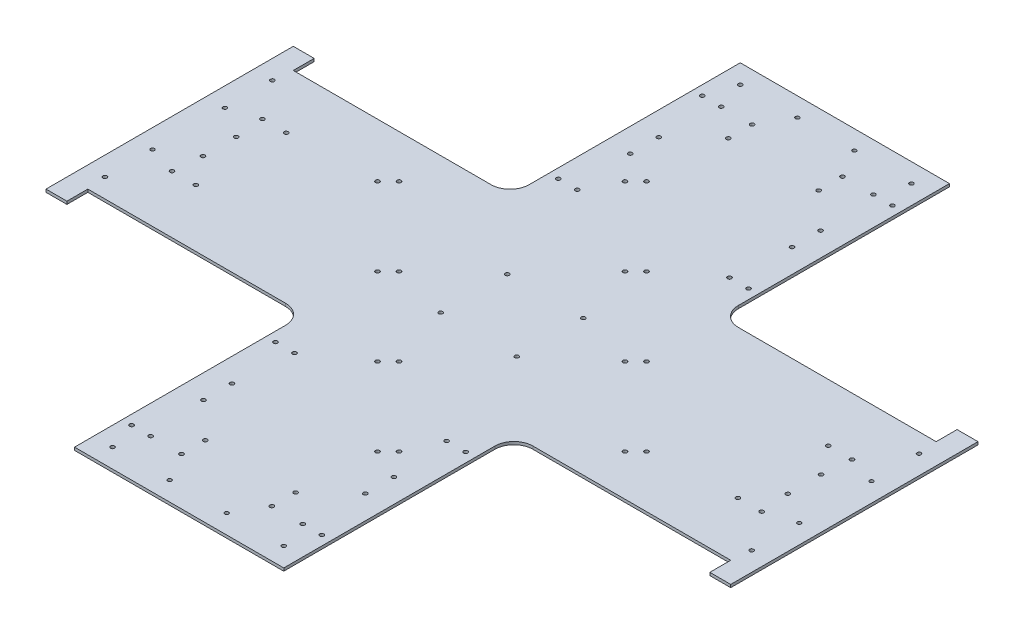
SolidWorks part; units mm, degrees
ref_plane "Front Plane" through (0, 0, 0) normal (0, 0, 1) x (1, 0, 0)
ref_plane "Top Plane" through (0, 0, 0) normal (0, 1, 0) x (1, 0, 0)
ref_plane "Right Plane" through (0, 0, 0) normal (1, 0, 0) x (0, 0, -1)
sketch "Sketch1" plane through (0, 0, 0) normal (0, 1, 0) x (1, 0, 0)
  line L0 (-110, 350) -> (-110, 108)
  line L1 (-110, 108) -> (-338, 108)
  line L2 (-338, 108) -> (-338, 130)
  line L3 (-338, 130) -> (-360, 130)
  line L4 (-360, 130) -> (-360, -130)
  line L5 (-360, 0) -> (1003.1457, 0) construction
  line L6 (0, 350) -> (0, -620.7989) construction
  line L7 (-338, -130) -> (-360, -130)
  line L8 (-338, -108) -> (-338, -130)
  line L9 (-110, -108) -> (-338, -108)
  line L10 (-110, 350) -> (110, 350)
  line L11 (-110, -350) -> (-110, -108)
  line L12 (-110, -350) -> (110, -350)
  line L13 (110, -350) -> (110, -108)
  line L14 (110, -108) -> (338, -108)
  line L15 (338, -108) -> (338, -130)
  line L16 (338, -130) -> (360, -130)
  line L17 (360, 130) -> (360, -130)
  line L18 (338, 130) -> (360, 130)
  line L19 (338, 108) -> (338, 130)
  line L20 (110, 108) -> (338, 108)
  line L21 (110, 350) -> (110, 108)
  point P17 (0, -350)
  dimension "D1" = 110
  dimension "D2" = 22
  dimension "D3" = 22
  dimension "D4" = 242
  dimension "D5" = 130
  dimension "D6" = 250
  dimension "D7" = 110
  dimension "D8" = 108
extrude "Boss-Extrude1" add sketch "Sketch1" along normal blind 3
sketch "Sketch2" plane through (0, 3, 0) normal (0, 1, 0) x (1, 0, 0)
  line L0 (360, -130) -> (360, 130) construction
  line L2 (338, 108) -> (110, 108) construction
  line L4 (0, 107.9437) -> (0, -458.275) construction
  line L5 (110, 108) -> (110, 350) construction
  line L6 (110, 350) -> (-110, 350) construction
  line L7 (-540.1841, 0) -> (-80.3508, 0) construction
  circle A0 centre (310, 47.5) radius 2.125
  circle A1 centre (285, 47.5) radius 2.125
  circle A2 centre (307.5, 17.5) radius 2.125
  circle A3 centre (307.5, -17.5) radius 2.125
  circle A4 centre (310, -47.5) radius 2.125
  circle A5 centre (285, -47.5) radius 2.125
  circle A6 centre (-285, -47.5) radius 2.125
  circle A7 centre (-310, -47.5) radius 2.125
  circle A8 centre (-307.5, -17.5) radius 2.125
  circle A9 centre (-307.5, 17.5) radius 2.125
  circle A10 centre (-285, 47.5) radius 2.125
  circle A11 centre (-310, 47.5) radius 2.125
  circle A13 centre (47.5, 300) radius 2.125
  circle A15 centre (47.5, 275) radius 2.125
  circle A16 centre (-47.5, 275) radius 2.125
  circle A17 centre (-47.5, 300) radius 2.125
  circle A18 centre (-47.5, -300) radius 2.125
  circle A19 centre (-47.5, -275) radius 2.125
  circle A20 centre (47.5, -275) radius 2.125
  circle A21 centre (47.5, -300) radius 2.125
  dimension "D1" = 4.25
  dimension "D2" = 4.25
  dimension "D3" = 4.25
  dimension "D4" = 4.25
  dimension "D5" = 4.25
  dimension "D6" = 4.25
  dimension "D15" = 4.25
  dimension "D16" = 4.25
  dimension "D7" = 50
  dimension "D8" = 25
  dimension "D9" = 95
  dimension "D10" = 35
  dimension "D11" = 60.5
  dimension "D12" = 90.5
  dimension "D13" = 52.5
  dimension "D14" = 110
  dimension "D17" = 50
  dimension "D18" = 25
  dimension "D19" = 62.5
  dimension "D20" = 108
extrude "Cut-Extrude1" cut sketch "Sketch2" against normal through all
sketch "Sketch3" plane through (0, 3, 0) normal (0, 1, 0) x (1, 0, 0)
  line L0 (360, -130) -> (360, 130) construction
  line L1 (338, 108) -> (110, 108) construction
  line L2 (-553.4456, 0) -> (-91.4299, 0) construction
  line L3 (0, 286.895) -> (0, -255.8046) construction
  line L4 (110, 108) -> (110, 350) construction
  line L5 (110, 350) -> (-110, 350) construction
  line L6 (-110, 350) -> (-110, 108) construction
  circle A0 centre (340, 38) radius 2
  circle A2 centre (340, -38) radius 2
  circle A3 centre (-340, -38) radius 2
  circle A4 centre (-340, 38) radius 2
  circle A5 centre (-30, 330) radius 2
  circle A7 centre (30, 330) radius 2
  circle A8 centre (30, -330) radius 2
  circle A9 centre (-30, -330) radius 2
  dimension "D1" = 4
  dimension "D6" = 4
  dimension "D7" = 80
  dimension "D2" = 20
  dimension "D3" = 70
  dimension "D4" = 108
  dimension "D5" = 110
  dimension "D8" = 20
extrude "Cut-Extrude2" cut sketch "Sketch3" against normal through all
sketch "Sketch5" plane through (0, 3, 0) normal (0, 1, 0) x (1, 0, 0)
  line L0 (110, 350) -> (-110, 350) construction
  line L1 (110, 108) -> (110, 350) construction
  line L2 (0, 224.365) -> (185.6725, 224.365) construction
  line L3 (90, 361.0488) -> (90, 126.2188) construction
  line L4 (0, 375.894) -> (0, 88.4107) construction
  line L5 (349.7475, 0) -> (-242.2654, 0) construction
  circle A0 centre (80, 300) radius 2.125
  circle A1 centre (80, 148.73) radius 2.125
  circle A2 centre (85.11, 239.365) radius 2.125
  circle A3 centre (85.11, 209.365) radius 2.125
  circle A4 centre (100, 148.73) radius 2.125
  circle A5 centre (100, 300) radius 2.125
  circle A6 centre (-100, 300) radius 2.125
  circle A7 centre (-100, 148.73) radius 2.125
  circle A8 centre (-85.11, 209.365) radius 2.125
  circle A9 centre (-85.11, 239.365) radius 2.125
  circle A10 centre (-80, 148.73) radius 2.125
  circle A11 centre (-80, 300) radius 2.125
  circle A12 centre (-80, -300) radius 2.125
  circle A13 centre (-80, -148.73) radius 2.125
  circle A14 centre (-85.11, -239.365) radius 2.125
  circle A15 centre (-85.11, -209.365) radius 2.125
  circle A16 centre (-100, -148.73) radius 2.125
  circle A17 centre (-100, -300) radius 2.125
  circle A18 centre (100, -300) radius 2.125
  circle A19 centre (100, -148.73) radius 2.125
  circle A20 centre (85.11, -209.365) radius 2.125
  circle A21 centre (85.11, -239.365) radius 2.125
  circle A22 centre (80, -148.73) radius 2.125
  circle A23 centre (80, -300) radius 2.125
  dimension "D1" = 4.25
  dimension "D2" = 4.25
  dimension "D6" = 4.25
  dimension "D7" = 4.25
  dimension "D3" = 151.27
  dimension "D4" = 50
  dimension "30" = 30
  dimension "D5" = 5.11
  dimension "D8" = 30
  dimension "D9" = 75.635
  dimension "D10" = 15
  dimension "D11" = 10
extrude "Cut-Extrude4" cut sketch "Sketch5" against normal blind 10
fillet "Fillet1" radius 20 4 edges at (110, 1.5, -108) (-110, 1.5, -108) (-110, 1.5, 108) (110, 1.5, 108)
sketch "Sketch6" plane through (0, 3, 0) normal (0, 1, 0) x (1, 0, 0)
  line L0 (-327.256, 327.256) -> (0, 0) construction
  line L1 (0, 429.479) -> (0, -412.5125) construction
  line L2 (-249.4214, 108) -> (110, -251.4214) construction
  line L3 (-226.7939, 108) -> (110, -228.7939) construction
  line L4 (327.256, 327.256) -> (0, 0) construction
  line L5 (-244.4559, 114.3482) -> (114.8318, -244.9395) construction
  line L6 (-130, 108) -> (-338, 108) construction
  line L7 (110, -350) -> (110, -128) construction
  circle A0 centre (53.3259, -194.7473) radius 2.125
  circle A1 centre (-192.7473, 51.3259) radius 2.125
  circle A2 centre (-28.6985, -112.7229) radius 2.125
  circle A3 centre (-110.7229, -30.6985) radius 2.125
  circle A4 centre (64.6396, -183.4335) radius 2.125
  circle A5 centre (-17.3848, -101.4092) radius 2.125
  circle A6 centre (-99.4092, -19.3848) radius 2.125
  circle A7 centre (-181.4335, 62.6396) radius 2.125
  circle A8 centre (-62.6396, 181.4335) radius 2.125
  circle A9 centre (19.3848, 99.4092) radius 2.125
  circle A10 centre (101.4092, 17.3848) radius 2.125
  circle A11 centre (183.4335, -64.6396) radius 2.125
  circle A12 centre (30.6985, 110.7229) radius 2.125
  circle A13 centre (112.7229, 28.6985) radius 2.125
  circle A14 centre (-51.3259, 192.7473) radius 2.125
  circle A15 centre (194.7473, -53.3259) radius 2.125
  point P23 (-69.7107, -71.7107)
  point P49 (71.7107, 69.7107)
  dimension "D3" = 4.25
  dimension "D5" = 4.25
  dimension "D8" = 4.25
  dimension "D10" = 4.25
  dimension "D1" = 45
  dimension "D2" = 100
  dimension "D4" = 16
  dimension "D6" = 348
  dimension "D7" = 174
  dimension "D9" = 116
  dimension "D11" = 116
  dimension "D12" = 8
extrude "Cut-Extrude5" cut sketch "Sketch6" against normal through all
sketch "Sketch7" plane through (0, 3, 0) normal (0, 1, 0) x (1, 0, 0)
  line L0 (0, 227.3539) -> (0, -244.3347) construction
  line L1 (-222.6371, 0) -> (245.907, 0) construction
  line L2 (360, -130) -> (360, 130) construction
  line L3 (338, 108) -> (130, 108) construction
  line L4 (110, 350) -> (-110, 350) construction
  line L5 (-110, 350) -> (-110, 128) construction
  circle A0 centre (340, 88) radius 2.1
  circle A1 centre (340, -88) radius 2.1
  circle A2 centre (-340, -88) radius 2.1
  circle A3 centre (-340, 88) radius 2.1
  circle A4 centre (-90, 330) radius 2.1
  circle A5 centre (90, 330) radius 2.1
  circle A6 centre (90, -330) radius 2.1
  circle A7 centre (-90, -330) radius 2.1
  dimension "D1" = 4.2
  dimension "D2" = 20
  dimension "D3" = 20
  dimension "D4" = 4.2
  dimension "D5" = 20
  dimension "D6" = 20
sketch "Sketch8" plane through (0, 3, 0) normal (0, 1, 0) x (1, 0, 0)
  line L0 (0, 227.3539) -> (0, -244.3347) construction
  line L1 (-222.6371, 0) -> (245.907, 0) construction
  line L2 (0, 89.3324) -> (0, -51.9249) construction
  line L3 (-114.1619, 0) -> (124.8762, 0) construction
  circle A0 centre (-40, 35) radius 2.1
  circle A1 centre (40, 35) radius 2.1
  circle A2 centre (40, -35) radius 2.1
  circle A3 centre (-40, -35) radius 2.1
  dimension "D1" = 4.2
  dimension "D2" = 40
  dimension "D3" = 35
extrude "Cut-Extrude6" cut sketch "Sketch8" against normal blind 10
extrude "Cut-Extrude7" cut sketch "Sketch7" against normal blind 10
equation "\"M3\"= 4.25mm"
equation "\"D1@Sketch2\"=\"M3\""
equation "\"D2@Sketch2\"=\"M3\""
equation "\"D3@Sketch2\"=\"M3\""
equation "\"D4@Sketch2\"=\"M3\""
equation "\"D5@Sketch2\"=\"M3\""
equation "\"D6@Sketch2\"=\"M3\""
equation "\"D15@Sketch2\"=\"M3\""
equation "\"D16@Sketch2\"=\"M3\""
equation "\"D6@Sketch5\"=\"M3\""
equation "\"D7@Sketch5\"=\"M3\""
equation "\"D2@Sketch5\"=\"M3\""
equation "\"D10@Sketch6\"=\"M3\""
equation "\"D3@Sketch6\"=\"M3\""
equation "\"D8@Sketch6\"=\"M3\""
equation "\"D5@Sketch6\"=\"M3\""
